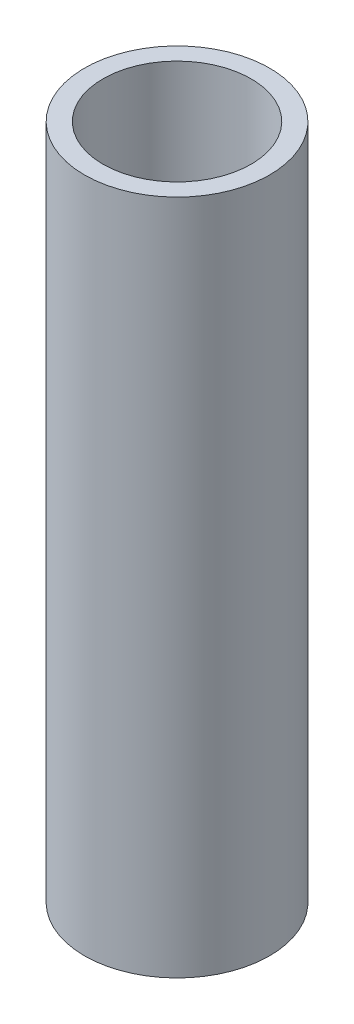
SolidWorks part; units mm, degrees
ref_plane "Front Plane" through (0, 0, 0) normal (0, 0, 1) x (1, 0, 0)
ref_plane "Top Plane" through (0, 0, 0) normal (0, 1, 0) x (1, 0, 0)
ref_plane "Right Plane" through (0, 0, 0) normal (1, 0, 0) x (0, 0, -1)
sketch "Sketch1" plane through (0, 0, 0) normal (0, 1, 0) x (1, 0, 0)
  circle A0 centre (0, 0) radius 3.75
  circle A1 centre (0, 0) radius 3
  dimension "D1" = 6
  dimension "D2" = 7.5
extrude "Boss-Extrude1" add sketch "Sketch1" along normal blind 27.3951
